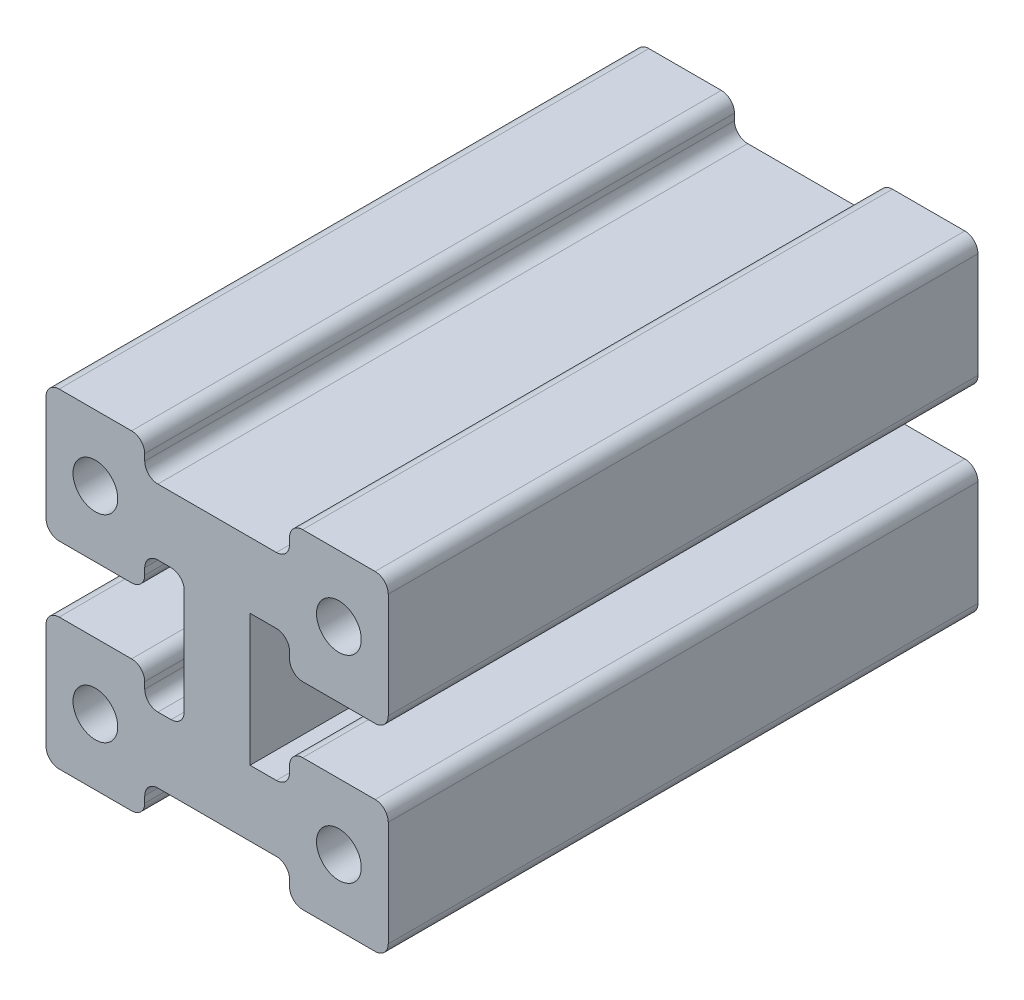
SolidWorks part; units mm, degrees
material "ABS"
ref_plane "Alzado" through (0, 0, 0) normal (1, 0, 0) x (0, 1, 0)
ref_plane "Planta" through (0, 0, 0) normal (0, 0, 1) x (0, 1, 0)
ref_plane "Vista lateral" through (0, 0, 0) normal (0, 1, 0) x (-1, 0, 0)
sketch "Croquis1" plane through (0, 0, 0) normal (0, 0, 1) x (0, 1, 0)
  line L0 (0, 0) -> (7.5, 0) construction
  line L1 (0, 0) -> (0, 13) construction
  line L2 (-5, 13) -> (5, 13)
  line L7 (5, 13) -> (5, 5.5)
  line L8 (5, 5.5) -> (2.5, 5.5)
  line L9 (2.5, 5.5) -> (2.5, 2.5)
  line L10 (-2.5, 5.5) -> (-2.5, -5.5)
  line L11 (-5, 5.5) -> (-2.5, 5.5)
  line L12 (-5, 13) -> (-5, 5.5)
  line L13 (5, -13) -> (5, -5.5)
  line L14 (5, -5.5) -> (2.5, -5.5)
  line L15 (-5, -5.5) -> (-2.5, -5.5)
  line L16 (-5, -13) -> (5, -13)
  line L17 (-5, -13) -> (-5, -5.5)
  line L18 (7.5, 0) -> (7.5, -14.6069) construction
  line L19 (15, 0) -> (15, 13) construction
  line L20 (20, -13) -> (20, -5.5)
  line L21 (20, -13) -> (10, -13)
  line L22 (20, -5.5) -> (17.5, -5.5)
  line L23 (10, -5.5) -> (12.5, -5.5)
  line L24 (10, -13) -> (10, -5.5)
  line L25 (20, 13) -> (20, 5.5)
  line L26 (20, 5.5) -> (17.5, 5.5)
  line L27 (17.5, 5.5) -> (17.5, -5.5)
  line L28 (12.5, 5.5) -> (12.5, 2.5)
  line L29 (10, 5.5) -> (12.5, 5.5)
  line L30 (10, 13) -> (10, 5.5)
  line L31 (20, 13) -> (10, 13)
  line L32 (2.5, 2.5) -> (12.5, 2.5)
  line L33 (2.5, -2.5) -> (12.5, -2.5)
  line L34 (2.5, -2.5) -> (2.5, -5.5)
  line L35 (12.5, -2.5) -> (12.5, -5.5)
  point P14 (-2.5, 0)
  point P15 (2.5, 0)
  point P33 (12.5, 0)
  point P34 (17.5, 0)
  dimension "D1" = 13
  dimension "D2" = 5
  dimension "D3" = 2.5
  dimension "D4" = 7.5
  dimension "D5" = 7.5
  dimension "D6" = 2.5
extrude "Saliente-Extruir1" add sketch "Croquis1" along normal mid plane 44.8
fillet "Redondeo1" radius 1 26 edges at (5.5, -2.5, 0) (5.5, -5, 0) (-5.5, -5, 0) (-5.5, -2.5, 0) (-5.5, 2.5, 0) (-5.5, 5, 0) (13, 5, 0) (5.5, 5, 0) (13, -5, 0) (-13, -5, 0) (-13, 5, 0) (5.5, 2.5, 0) (-5.5, 12.5, 0) (-5.5, 17.5, 0) (-13, 20, 0) (-5.5, 20, 0) (13, 20, 0) (5.5, 20, 0) (5.5, 17.5, 0) (-2.5, 2.5, 0) (-2.5, 12.5, 0) (-5.5, 10, 0) (-13, 10, 0) (13, 10, 0) (5.5, 12.5, 0) (5.5, 10, 0)
sketch "Croquis2" plane through (0, 0, -22.4) normal (0, 0, -1) x (1, 0, 0)
  line L0 (-13, 0) -> (13, 0) construction
  line L1 (-13, -4) -> (-13, 4) construction
  line L2 (13, 4) -> (13, -4) construction
  line L3 (0, 7.565) -> (0, 0) construction
  line L4 (2.5, -7.5) -> (14.5945, -7.5) construction
  line L5 (2.5, -2.5) -> (2.5, -12.5) construction
  point P9 (-9.25, 0)
  point P11 (9.25, 0)
  point P17 (9.25, -15)
  point P18 (-9.25, -15)
  dimension "D1" = 9.25
hole_wizard "Taladro de margen para M31" positions "Croquis2" profile "Croquis3" hole size "M3" standard "Ansi Metric" end condition through all
sketch "Croquis3" plane through (-9.25, 15, -22.4) normal (1, 0, 0) x (0, 1, 0)
  line L0 (0, 0) -> (0, 44.8)
  line L1 (0, 44.8) -> (1.7, 44.8)
  line L2 (1.7, 44.8) -> (1.7, 0)
  line L5 (1.7, 0) -> (0, 0)
  line L11 (0, -6.35) -> (0, 107.95) construction
  dimension "Diámetro de taladro hasta el siguiente" = 3.4
  dimension "Profundidad de taladro hasta el siguiente" = 44.8
